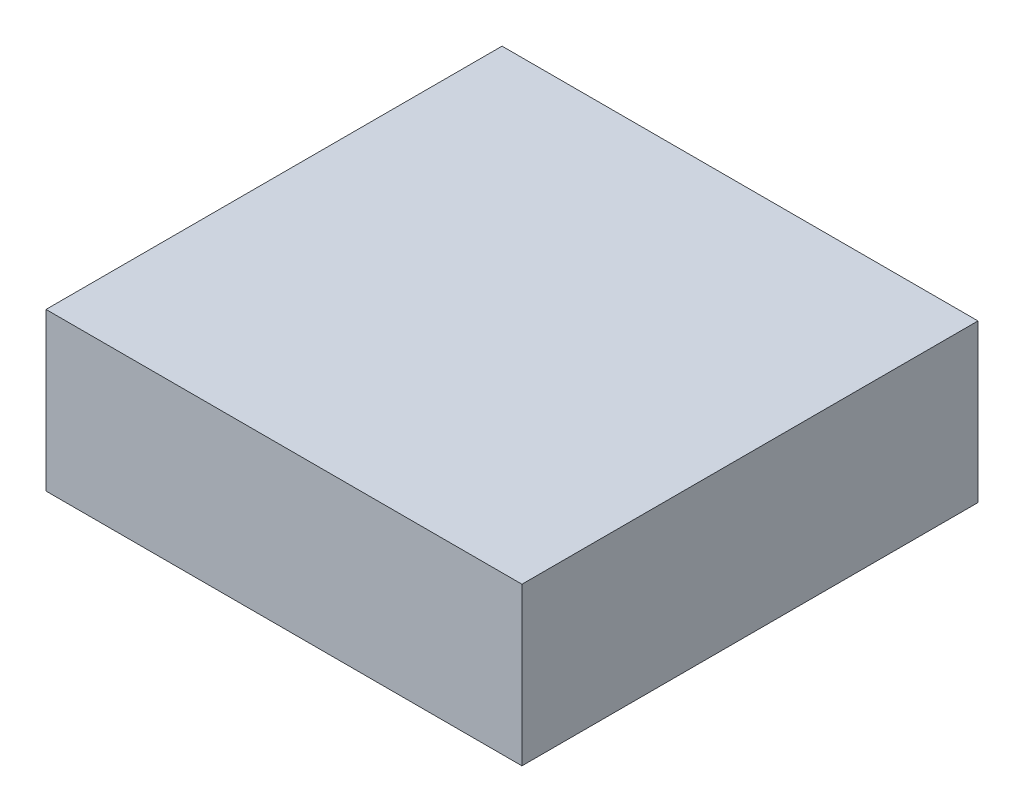
SolidWorks part; units mm, degrees
ref_plane "Front Plane" through (0, 0, 0) normal (0, 0, 1) x (1, 0, 0)
ref_plane "Top Plane" through (0, 0, 0) normal (0, 1, 0) x (1, 0, 0)
ref_plane "Right Plane" through (0, 0, 0) normal (1, 0, 0) x (0, 0, -1)
sketch "Sketch2" plane through (0, 0, 0) normal (0, 1, 0) x (1, 0, 0)
  line L1 (-11.95, 11.45) -> (11.95, 11.45)
  line L2 (-11.95, 11.45) -> (-11.95, -11.45)
  line L3 (-11.95, -11.45) -> (11.95, -11.45)
  line L4 (11.95, 11.45) -> (11.95, -11.45)
  line L5 (-11.95, 11.45) -> (11.95, -11.45) construction
  line L6 (-11.95, -11.45) -> (11.95, 11.45) construction
  point P0 (0, 0)
  dimension "D1" = 23.9
  dimension "D2" = 22.9
extrude "Boss-Extrude1" add sketch "Sketch2" along normal blind 7.9
